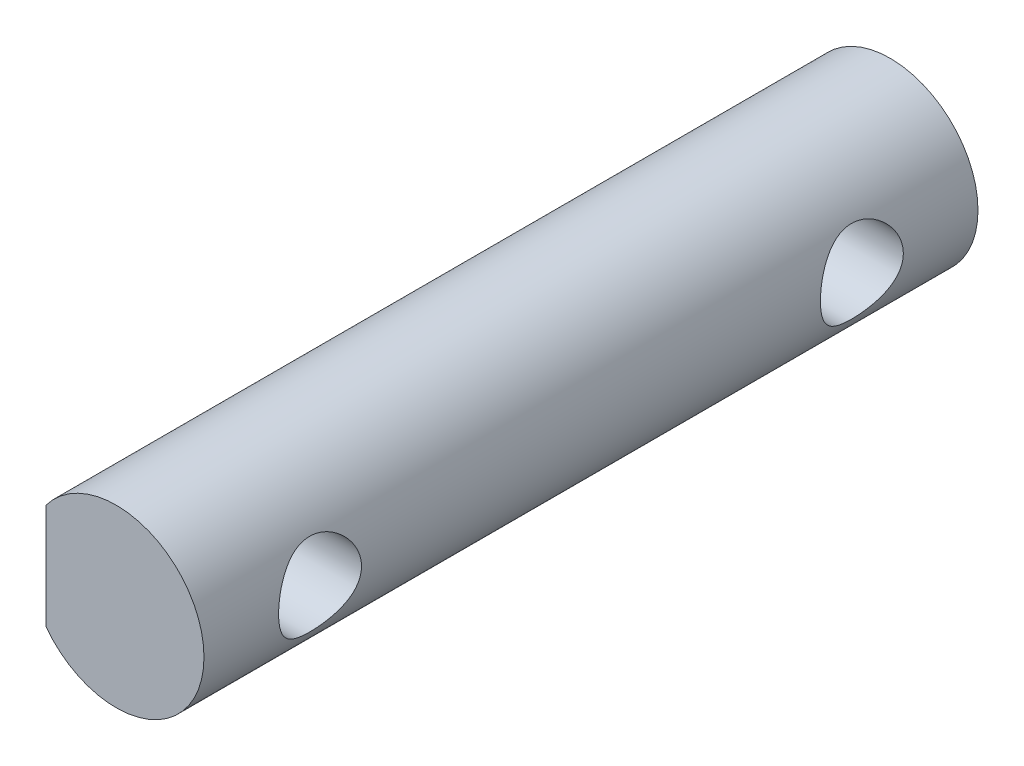
SolidWorks part; units mm, degrees
ref_plane "Front Plane" through (0, 0, 0) normal (0, 0, 1) x (1, 0, 0)
ref_plane "Top Plane" through (0, 0, 0) normal (0, 1, 0) x (1, 0, 0)
ref_plane "Right Plane" through (0, 0, 0) normal (1, 0, 0) x (0, 0, -1)
sketch "Sketch1" plane through (0, 0, 0) normal (0, 0, 1) x (1, 0, 0)
  line L0 (-2.54, 1.905) -> (-2.54, -1.905)
  arc A0 (-2.54, -1.905) -> (-2.54, 1.905) centre (0, 0) ccw
  point P5 (3.175, 0)
  dimension "D1" = 6.35
  dimension "D2" = 5.715
extrude "Boss-Extrude1" add sketch "Sketch1" along normal blind 28
sketch "Sketch3" plane through (-2.54, 0, 0) normal (-1, 0, 0) x (0, 0, 1)
  line L0 (4.2, 0) -> (23.8, 0) construction
  line L1 (28, -1.905) -> (0, -1.905) construction
  circle A0 centre (4.2, 0) radius 1.5
  circle A1 centre (23.8, 0) radius 1.5
  point P5 (14, -1.905)
  point P6 (14, 0)
  point P8 (23.8, 0)
  point P10 (23.8, 0.1514)
  dimension "D2" = 3
  dimension "D1" = 19.6
extrude "Cut-Extrude1" cut sketch "Sketch3" against normal up to surface (5.715 mm away)
